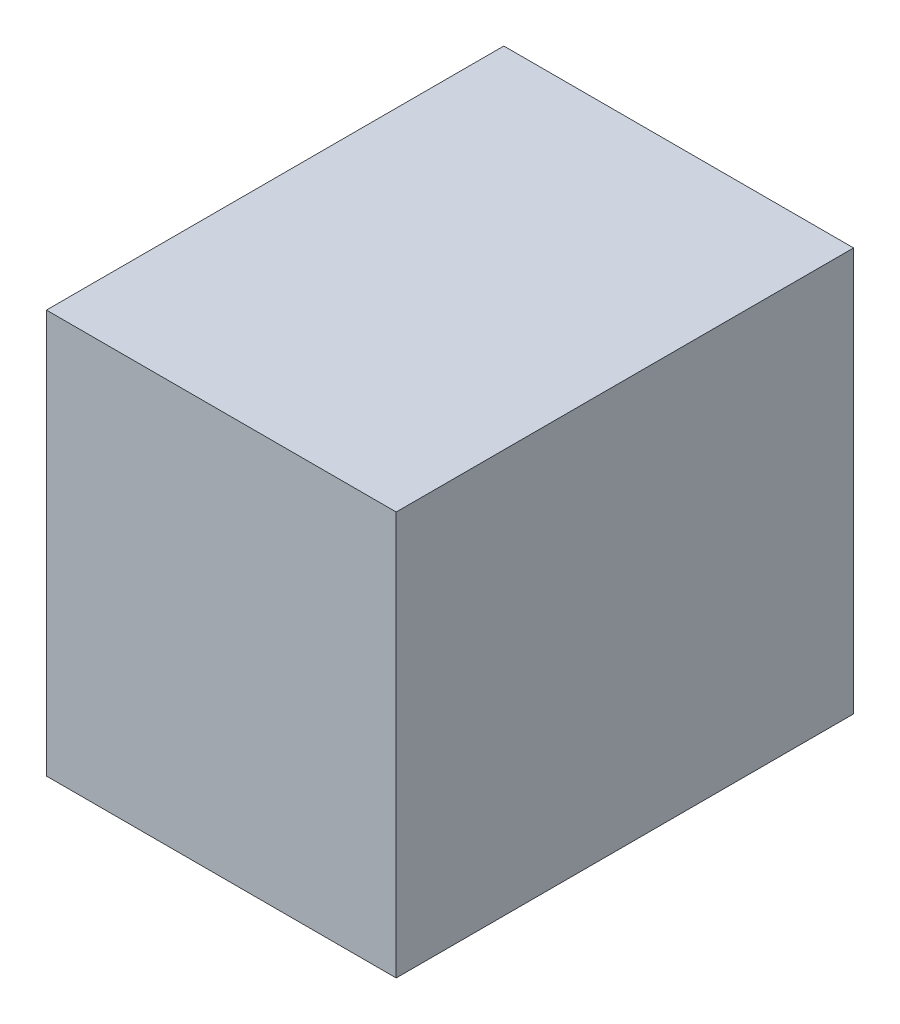
SolidWorks part; units mm, degrees
ref_plane "Front Plane" through (0, 0, 0) normal (0, 0, 1) x (1, 0, 0)
ref_plane "Top Plane" through (0, 0, 0) normal (0, 1, 0) x (1, 0, 0)
ref_plane "Right Plane" through (0, 0, 0) normal (1, 0, 0) x (0, 0, -1)
sketch "Sketch1" plane through (0, 0, 0) normal (0, 1, 0) x (1, 0, 0)
  line L1 (-6.5, -8.5) -> (6.5, -8.5)
  line L2 (-6.5, -8.5) -> (-6.5, 8.5)
  line L3 (-6.5, 8.5) -> (6.5, 8.5)
  line L4 (6.5, -8.5) -> (6.5, 8.5)
  line L5 (-6.5, -8.5) -> (6.5, 8.5) construction
  line L6 (-6.5, 8.5) -> (6.5, -8.5) construction
  point P0 (0, 0)
  dimension "D1" = 13
  dimension "D2" = 17
extrude "Boss-Extrude1" add sketch "Sketch1" along normal blind 15
